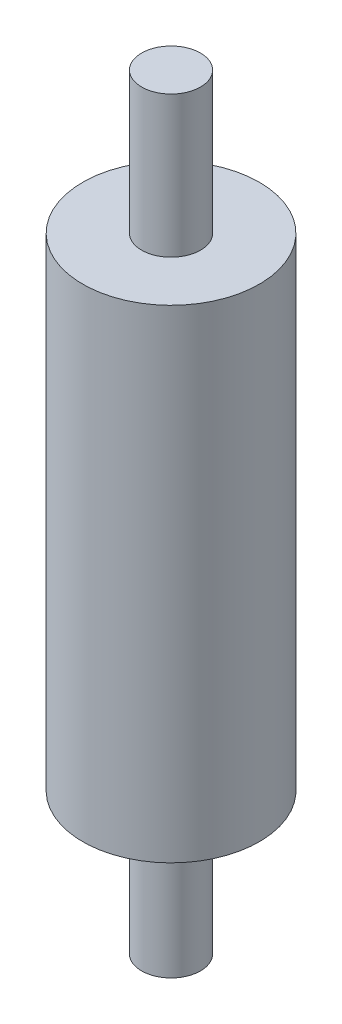
SolidWorks part; units mm, degrees
ref_plane "Front Plane" through (0, 0, 0) normal (0, 0, 1) x (1, 0, 0)
ref_plane "Top Plane" through (0, 0, 0) normal (0, 1, 0) x (1, 0, 0)
ref_plane "Right Plane" through (0, 0, 0) normal (1, 0, 0) x (0, 0, -1)
sketch "Sketch1" plane through (0, 0, 0) normal (1, 0, 0) x (0, 0, -1)
  line L0 (0, -32.5) -> (2.5, -32.5)
  line L1 (2.5, -32.5) -> (2.5, -20.5)
  line L2 (2.5, -20.5) -> (7.5, -20.5)
  line L3 (7.5, -20.5) -> (7.5, 20.5)
  line L4 (7.5, 20.5) -> (2.5, 20.5)
  line L5 (2.5, 20.5) -> (2.5, 32.5)
  line L6 (2.5, 32.5) -> (0, 32.5)
  line L7 (0, 32.5) -> (0, -32.5)
  line L8 (0, 0) -> (0, 62.5912) construction
  dimension "D1" = 41
  dimension "D2" = 5
  dimension "D3" = 5
  dimension "D4" = 15
  dimension "D5" = 12
revolve "Revolve1" add sketch "Sketch1" angle 360 about L8
cosmetic thread "Cosmetic Thread1" parameters "D2"=3.22
cosmetic thread "Cosmetic Thread2" parameters "D2"=3.22
